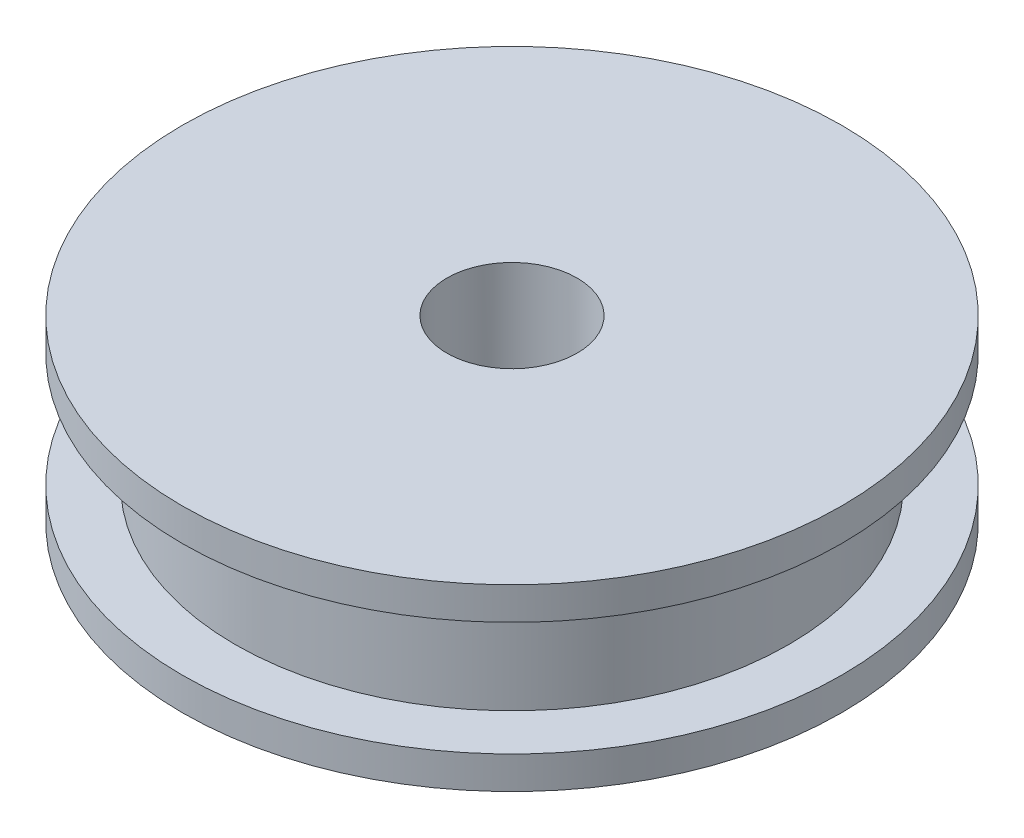
SolidWorks part; units mm, degrees
ref_plane "Front Plane" through (0, 0, 0) normal (0, 0, 1) x (1, 0, 0)
ref_plane "Top Plane" through (0, 0, 0) normal (0, 1, 0) x (1, 0, 0)
ref_plane "Right Plane" through (0, 0, 0) normal (1, 0, 0) x (0, 0, -1)
sketch "Sketch1" plane through (0, 0, 0) normal (0, 0, 1) x (1, 0, 0)
  line L0 (0, 0) -> (0, 18) construction
  line L1 (-4, 0) -> (-4, 18)
  line L2 (-4, 18) -> (-20.25, 18)
  line L3 (-20.25, 18) -> (-20.25, 16)
  line L4 (-20.25, 16) -> (-17, 16)
  line L5 (-17, 16) -> (-17, 9)
  line L6 (-17, 9) -> (-20.25, 9)
  line L7 (-20.25, 9) -> (-20.25, 7)
  line L8 (-20.25, 7) -> (-10, 7)
  line L9 (-10, 7) -> (-10, 0)
  line L10 (-10, 0) -> (-4, 0)
  dimension "D1" = 18
  dimension "D2" = 20.25
  dimension "D3" = 2
  dimension "D4" = 11
  dimension "D5" = 10
  dimension "D6" = 17
  dimension "D7" = 4
revolve "Revolve1" add sketch "Sketch1" angle 360 about L0
sketch "Sketch2" plane through (0, 0, 0) normal (0, 0, 1) x (1, 0, 0)
  line L0 (0, 7) -> (0, 0) construction
  line L1 (-10, 7) -> (10, 7) construction
  circle A0 centre (0, 3.5) radius 2
  point P7 (0, 0)
  point P8 (0, 3.5)
  dimension "D1" = 4
extrude "Cut-Extrude1" cut sketch "Sketch2" against normal through all
pattern_circular "CirPattern1" count 2 over 90 about axis through (0, 0, 0) along (0, -1, 0) of "Cut-Extrude1"
